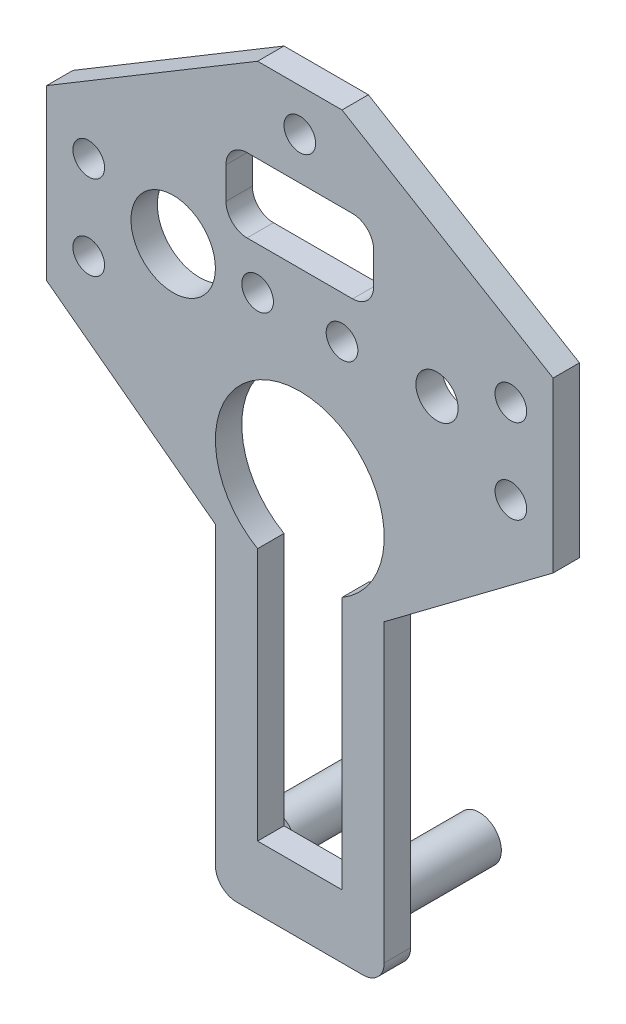
SolidWorks part; units mm, degrees
ref_plane "Front Plane" through (0, 0, 0) normal (0, 0, 1) x (1, 0, 0)
ref_plane "Top Plane" through (0, 0, 0) normal (0, 1, 0) x (1, 0, 0)
ref_plane "Right Plane" through (0, 0, 0) normal (1, 0, 0) x (0, 0, -1)
sketch "Sketch1" plane through (0, 0, 0) normal (0, 0, 1) x (1, 0, 0)
  line L0 (-24, 5.0718) -> (-24, 21.0718)
  line L1 (-24, 21.0718) -> (-4, 33.0718)
  line L2 (-4, 33.0718) -> (4, 33.0718)
  line L3 (4, 33.0718) -> (24, 21.0718)
  line L4 (24, 21.0718) -> (24, 5.0718)
  line L5 (24, 5.0718) -> (8, -6.9282)
  line L6 (8, -6.9282) -> (8, -34.9282)
  line L7 (-6, -36.9282) -> (6, -36.9282)
  line L8 (-8, -34.9282) -> (-8, -6.9282)
  line L9 (-8, -6.9282) -> (-24, 5.0718)
  line L10 (4, -30.9282) -> (-4, -30.9282)
  line L11 (-4, -30.9282) -> (-4, -6.9282)
  line L12 (4, -6.9282) -> (4, -30.9282)
  line L13 (-5, 25.0718) -> (5, 25.0718)
  line L14 (7, 23.0718) -> (7, 20.0718)
  line L15 (-7, 23.0718) -> (-7, 20.0718)
  line L16 (-5, 18.0718) -> (5, 18.0718)
  arc A0 (-4, -6.9282) -> (4, -6.9282) centre (0, 0) cw
  arc A1 (5, 25.0718) -> (7, 23.0718) centre (5, 23.0718) cw
  arc A2 (-5, 25.0718) -> (-7, 23.0718) centre (-5, 23.0718) ccw
  arc A3 (-7, 20.0718) -> (-5, 18.0718) centre (-5, 20.0718) ccw
  arc A4 (5, 18.0718) -> (7, 20.0718) centre (5, 20.0718) ccw
  circle A5 centre (-12, 14.0718) radius 4
  circle A6 centre (-4, 14.0718) radius 1.5
  circle A7 centre (4, 14.0718) radius 1.5
  circle A8 centre (0, 29.0718) radius 1.5
  circle A9 centre (20, 17.0718) radius 1.5
  circle A10 centre (20, 9.0718) radius 1.5
  circle A11 centre (-20, 17.0718) radius 1.5
  circle A12 centre (-20, 9.0718) radius 1.5
  circle A13 centre (13, 14.0718) radius 2
  arc A14 (-8, -34.9282) -> (-6, -36.9282) centre (-6, -34.9282) ccw
  arc A15 (6, -36.9282) -> (8, -34.9282) centre (6, -34.9282) ccw
  dimension "D1" = 28
  dimension "D4" = 12
  dimension "D7" = 4
  dimension "D8" = 4
  dimension "D9" = 2
  dimension "D10" = 8
  dimension "D19" = 8
  dimension "D20" = 10
  dimension "D22" = 2
  dimension "D18" = 8
  dimension "D24" = 3
  dimension "D25" = 4
  dimension "D31" = 4
  dimension "D3" = 8
  dimension "D5" = 8
  dimension "D6" = 24
  dimension "D11" = 6
  dimension "D12" = 16
  dimension "D13" = 17
  dimension "D14" = 20
  dimension "D15" = 48
  dimension "D16" = 24
  dimension "D17" = 20
  dimension "D21" = 3
  dimension "D23" = 12
  dimension "D26" = 4
  dimension "D27" = 4
  dimension "D28" = 4
  dimension "D29" = 4
  dimension "D30" = 4
  dimension "D32" = 20
  dimension "D33" = 70
  dimension "D34" = 24
  dimension "D35" = 120.964
  dimension "D36" = 11
extrude "Boss-Extrude1" add sketch "Sketch1" along normal blind 2.5
sketch "Sketch2" plane through (0, 0, 0) normal (0, 0, -1) x (-1, 0, 0)
  line L0 (-5, -32.1616) -> (5, -32.1616) construction
  circle A0 centre (-5, -32.1616) radius 2.1
  circle A2 centre (5, -32.1616) radius 2.1
sketch "Sketch3" plane through (-24, 0, 0) normal (-1, 0, 0) x (0, 0, 1)
extrude "Boss-Extrude2" add sketch "Sketch2" along normal blind 9.5
